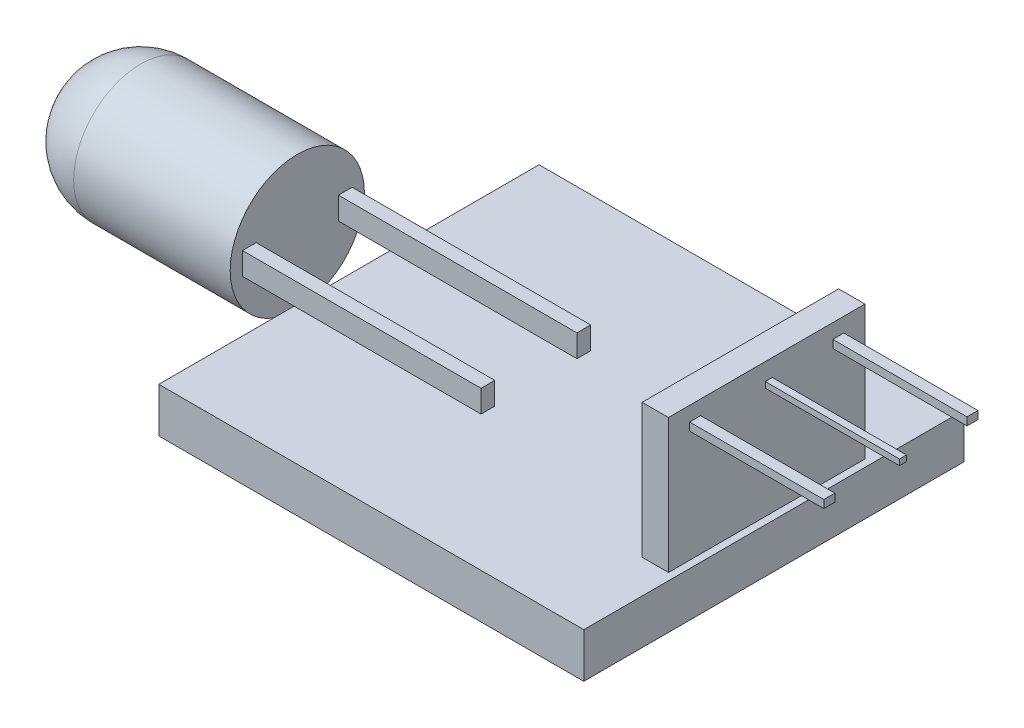
SolidWorks part; units mm, degrees
ref_plane "Plan de face" through (0, 0, 0) normal (0, 0, 1) x (1, 0, 0)
ref_plane "Plan de dessus" through (0, 0, 0) normal (0, 1, 0) x (1, 0, 0)
ref_plane "Plan de droite" through (0, 0, 0) normal (1, 0, 0) x (0, 0, -1)
sketch "Esquisse1" plane through (0, 0, 0) normal (0, 1, 0) x (1, 0, 0)
  line L1 (-9.5, 8.5) -> (9.5, 8.5)
  line L2 (-9.5, 8.5) -> (-9.5, -8.5)
  line L3 (-9.5, -8.5) -> (9.5, -8.5)
  line L4 (9.5, 8.5) -> (9.5, -8.5)
  line L5 (-9.5, 8.5) -> (9.5, -8.5) construction
  line L6 (-9.5, -8.5) -> (9.5, 8.5) construction
  point P0 (0, 0)
  dimension "D1" = 17
  dimension "D2" = 19
extrude "Boss.-Extru.1" add sketch "Esquisse1" along normal blind 2
sketch "Esquisse2" plane through (0, 2, 0) normal (0, 1, 0) x (1, 0, 0)
  line L1 (9.1778, -4.3926) -> (8.0011, -4.3926)
  line L2 (9.1778, -4.3926) -> (9.1778, 4.3926)
  line L3 (9.1778, 4.3926) -> (8.0011, 4.3926)
  line L4 (8.0011, -4.3926) -> (8.0011, 4.3926)
  line L5 (9.1778, -4.3926) -> (8.0011, 4.3926) construction
  line L6 (9.1778, 4.3926) -> (8.0011, -4.3926) construction
  point P0 (8.5895, 0)
extrude "Boss.-Extru.2" add sketch "Esquisse2" along normal blind 6
sketch "Esquisse3" plane through (9.1778, 0, 0) normal (1, 0, 0) x (0, 0, -1)
  line L1 (-3.4464, 7.3513) -> (-2.954, 7.3513)
  line L2 (-3.4464, 7.3513) -> (-3.4464, 6.9997)
  line L3 (-3.4464, 6.9997) -> (-2.954, 6.9997)
  line L4 (-2.954, 7.3513) -> (-2.954, 6.9997)
extrude "Boss.-Extru.3" add sketch "Esquisse3" along normal blind 6
mirror "Symétrie1" about plane through (0, 0, 0) normal (0, 0, 1) of "Boss.-Extru.3"
sketch "Esquisse4" plane through (9.1778, 0, 0) normal (1, 0, 0) x (0, 0, -1)
  line L1 (-0.0644, 7.2288) -> (0.2488, 7.2288)
  line L2 (-0.0644, 7.2288) -> (-0.0644, 6.9711)
  line L3 (-0.0644, 6.9711) -> (0.2488, 6.9711)
  line L4 (0.2488, 7.2288) -> (0.2488, 6.9711)
extrude "Boss.-Extru.4" add sketch "Esquisse4" along normal blind 6
sketch "Esquisse5" plane through (0, 2, 0) normal (0, 1, 0) x (1, 0, 0)
  line L1 (-1.8066, -1.8378) -> (-1.143, -1.8378)
  line L2 (-1.8066, -1.8378) -> (-1.8066, -2.4504)
  line L3 (-1.8066, -2.4504) -> (-1.143, -2.4504)
  line L4 (-1.143, -1.8378) -> (-1.143, -2.4504)
extrude "Boss.-Extru.5" add sketch "Esquisse5" along normal blind 1
sketch "Esquisse6" plane through (-1.8066, 0, 0) normal (-1, 0, 0) x (0, 0, 1)
  line L1 (1.8378, 2) -> (2.4504, 2)
  line L2 (1.8378, 2) -> (1.8378, 3)
  line L3 (1.8378, 3) -> (2.4504, 3)
  line L4 (2.4504, 2) -> (2.4504, 3)
extrude "Boss.-Extru.6" add sketch "Esquisse6" along normal blind 10
mirror "Symétrie2" about plane through (0, 0, 0) normal (0, 0, 1) of "Boss.-Extru.5", "Boss.-Extru.6"
ref_plane "Plan1" through (-11.8066, 0, 0) normal (-1, 0, 0) x (0, 0, 1)
sketch "Esquisse7" plane through (-11.8066, 0, 0) normal (-1, 0, 0) x (0, 0, 1)
  line L0 (-2.4504, 2.5) -> (2.4504, 2.5) construction
  line L1 (-2.4504, 2) -> (-2.4504, 3) construction
  line L2 (2.4504, 2) -> (2.4504, 3) construction
  circle A0 centre (0, 2.5) radius 3
  dimension "D1" = 6
extrude "Boss.-Extru.7" add sketch "Esquisse7" along normal blind 10
fillet "Congé2" radius 3 1 edges at (-21.8066, 2.5, 3)
